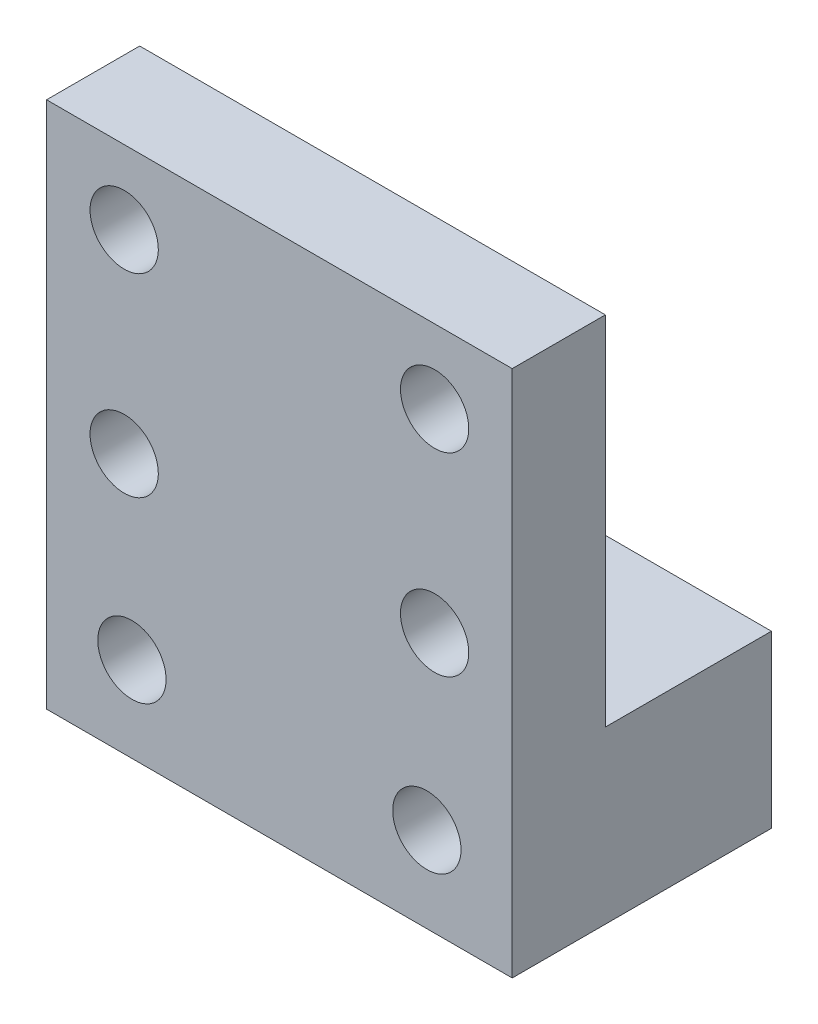
SolidWorks part; units mm, degrees
ref_plane "Front Plane" through (0, 0, 0) normal (0, 0, 1) x (1, 0, 0)
ref_plane "Top Plane" through (0, 0, 0) normal (0, 1, 0) x (1, 0, 0)
ref_plane "Right Plane" through (0, 0, 0) normal (1, 0, 0) x (0, 0, -1)
ref_plane "Plane1" through (0, 0, -8.3) normal (0, 0, 1) x (1, 0, 0)
sketch "Sketch1" plane through (0, 0, -8.3) normal (0, 0, 1) x (1, 0, 0)
  line L0 (-41.5, 29.5) -> (-41.5, -4.5)
  line L1 (-41.5, -4.5) -> (-11.5, -4.5)
  line L2 (-11.5, -4.5) -> (-11.5, 29.5)
  line L3 (-11.5, 29.5) -> (-41.5, 29.5)
extrude "Boss-Extrude1" add sketch "Sketch1" against normal blind 16.7
sketch "Sketch2" plane through (-41.5, 0, 0) normal (-1, 0, 0) x (0, 0, 1)
  line L0 (-14.3, 6.5) -> (-14.3, 29.5)
  line L1 (-14.3, 29.5) -> (-25, 29.5)
  line L2 (-25, 29.5) -> (-25, 6.5)
  line L3 (-25, 6.5) -> (-14.3, 6.5)
extrude "Cut-Extrude1" cut sketch "Sketch2" against normal through all
hole_wizard "Hole1" positions "Sketch4" profile "Sketch3" legacy
sketch "Sketch4" plane through (0, 0, -14.3) normal (0, 0, -1) x (-1, 0, 0)
  point P0 (16.5, 12.25)
sketch "Sketch3" plane through (-16.5, 12.25, -14.3) normal (1, 0, 0) x (0, 1, 0)
  line L0 (0, 0) -> (0, 6)
  line L1 (0, 6) -> (2.2, 6)
  line L2 (2.2, 6) -> (2.2, 0)
  line L3 (2.2, 0) -> (0, 0)
  line L4 (0, 110) -> (0, -10) construction
  dimension "Diameter" = 4.4
  dimension "Depth" = 6
hole_wizard "Hole2" positions "Sketch6" profile "Sketch5" legacy
sketch "Sketch6" plane through (0, 0, -14.3) normal (0, 0, -1) x (-1, 0, 0)
  point P0 (36.5, 12.25)
sketch "Sketch5" plane through (-36.5, 12.25, -14.3) normal (1, 0, 0) x (0, 1, 0)
  line L0 (0, 0) -> (0, 6)
  line L1 (0, 6) -> (2.2, 6)
  line L2 (2.2, 6) -> (2.2, 0)
  line L3 (2.2, 0) -> (0, 0)
  line L4 (0, 110) -> (0, -10) construction
  dimension "Diameter" = 4.4
  dimension "Depth" = 6
hole_wizard "Hole3" positions "Sketch8" profile "Sketch7" legacy
sketch "Sketch8" plane through (0, 0, -14.3) normal (0, 0, -1) x (-1, 0, 0)
  point P0 (36.5, 24.75)
sketch "Sketch7" plane through (-36.5, 24.75, -14.3) normal (1, 0, 0) x (0, 1, 0)
  line L0 (0, 0) -> (0, 6)
  line L1 (0, 6) -> (2.2, 6)
  line L2 (2.2, 6) -> (2.2, 0)
  line L3 (2.2, 0) -> (0, 0)
  line L4 (0, 110) -> (0, -10) construction
  dimension "Diameter" = 4.4
  dimension "Depth" = 6
hole_wizard "Hole4" positions "Sketch10" profile "Sketch9" legacy
sketch "Sketch10" plane through (0, 0, -14.3) normal (0, 0, -1) x (-1, 0, 0)
  point P0 (16.5, 24.75)
sketch "Sketch9" plane through (-16.5, 24.75, -14.3) normal (1, 0, 0) x (0, 1, 0)
  line L0 (0, 0) -> (0, 6)
  line L1 (0, 6) -> (2.2, 6)
  line L2 (2.2, 6) -> (2.2, 0)
  line L3 (2.2, 0) -> (0, 0)
  line L4 (0, 110) -> (0, -10) construction
  dimension "Diameter" = 4.4
  dimension "Depth" = 6
hole_wizard "Hole5" positions "Sketch12" profile "Sketch11" legacy
sketch "Sketch12" plane through (0, 0, -25) normal (0, 0, -1) x (-1, 0, 0)
  point P0 (36, 1)
sketch "Sketch11" plane through (-36, 1, -25) normal (1, 0, 0) x (0, 1, 0)
  line L0 (0, 0) -> (0, 16.7)
  line L1 (0, 16.7) -> (2.2, 16.7)
  line L2 (2.2, 16.7) -> (2.2, 0)
  line L3 (2.2, 0) -> (0, 0)
  line L4 (0, 110) -> (0, -10) construction
  dimension "Diameter" = 4.4
  dimension "Depth" = 16.7
hole_wizard "Hole6" positions "Sketch14" profile "Sketch13" legacy
sketch "Sketch14" plane through (0, 0, -8.3) normal (0, 0, 1) x (1, 0, 0)
  point P0 (-17, 1)
sketch "Sketch13" plane through (-17, 1, -8.3) normal (1, 0, 0) x (0, -1, 0)
  line L0 (0, 0) -> (0, 16.7)
  line L1 (0, 16.7) -> (2.2, 16.7)
  line L2 (2.2, 16.7) -> (2.2, 0)
  line L3 (2.2, 0) -> (0, 0)
  line L4 (0, 110) -> (0, -10) construction
  dimension "Diameter" = 4.4
  dimension "Depth" = 16.7
hole_wizard "Hole7" positions "Sketch16" profile "Sketch15" legacy
sketch "Sketch16" plane through (0, -4.5, 0) normal (0, -1, 0) x (1, 0, 0)
  point P0 (-26.5, -25)
sketch "Sketch15" plane through (-26.5, -4.5, -25) normal (1, 0, 0) x (0, 0, -1)
  line L0 (0, 0) -> (0, 34)
  line L1 (0, 34) -> (4, 34)
  line L2 (4, 34) -> (4, 0)
  line L3 (4, 0) -> (0, 0)
  line L4 (0, 110) -> (0, -10) construction
  dimension "Diameter" = 8
  dimension "Depth" = 34
ref_plane "Plane2" through (-26.5, 0, 0) normal (-1, 0, 0) x (0, -1, 0)
sketch "Sketch17" plane through (-26.5, 0, 0) normal (-1, 0, 0) x (0, -1, 0)
  line L0 (-29.5, -14.3) -> (-6.5, -21)
rib "Rib1" sketch "Sketch17" sketch "Sketch17" thickness 5 extrusion direction parallel to sketch draft on no parameters "D1"=5
